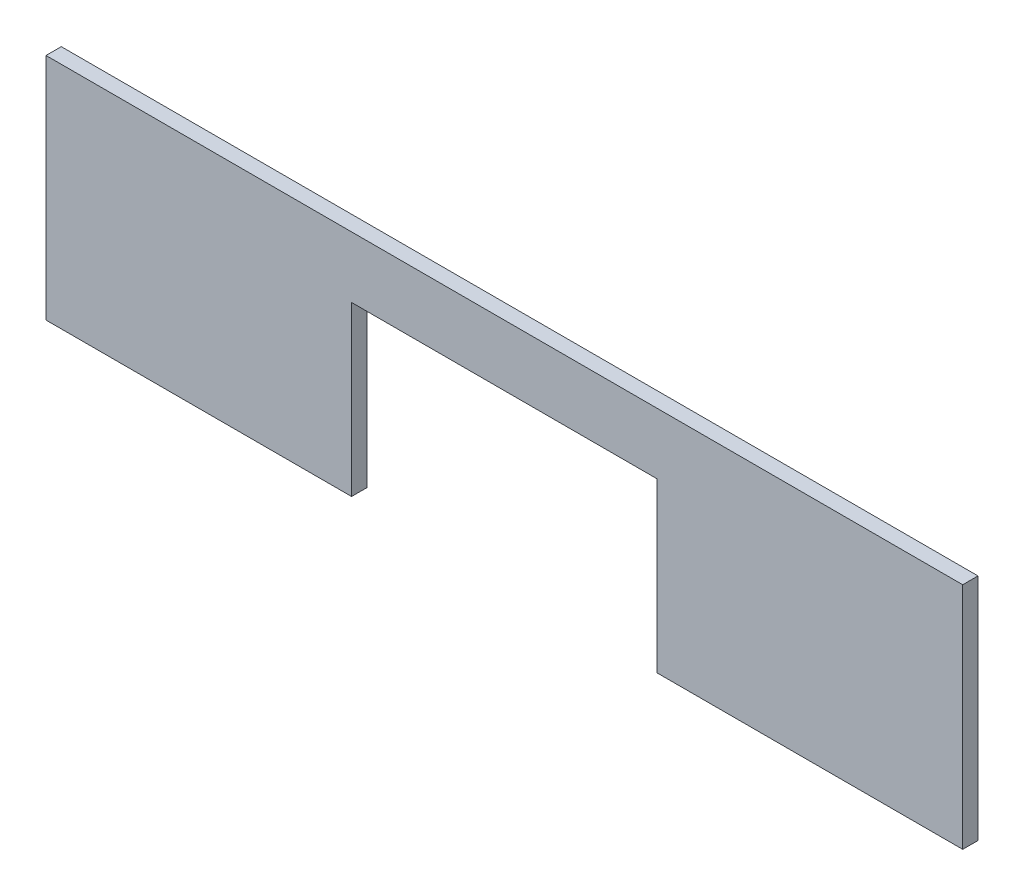
SolidWorks part; units mm, degrees
ref_plane "Front Plane" through (0, 0, 0) normal (0, 0, 1) x (1, 0, 0)
ref_plane "Top Plane" through (0, 0, 0) normal (0, 1, 0) x (1, 0, 0)
ref_plane "Right Plane" through (0, 0, 0) normal (1, 0, 0) x (0, 0, -1)
sketch "Sketch1" plane through (0, 0, 0) normal (0, 0, 1) x (1, 0, 0)
  line L1 (-300, -75) -> (300, -75)
  line L2 (-300, -75) -> (-300, 75)
  line L3 (-300, 75) -> (300, 75)
  line L4 (300, -75) -> (300, 75)
  line L5 (-300, -75) -> (300, 75) construction
  line L6 (-300, 75) -> (300, -75) construction
  line L7 (-100, -75) -> (100, -75)
  line L8 (-100, -75) -> (-100, 35)
  line L9 (-100, 35) -> (100, 35)
  line L10 (100, -75) -> (100, 35)
  point P0 (0, 0)
  point P10 (0, 35)
  dimension "D1" = 600
  dimension "D2" = 150
  dimension "D3" = 200
  dimension "D4" = 110
extrude "Boss-Extrude1" add sketch "Sketch1" along normal blind 10 contours L10 L1 L4 L3 L2 L8 L9
